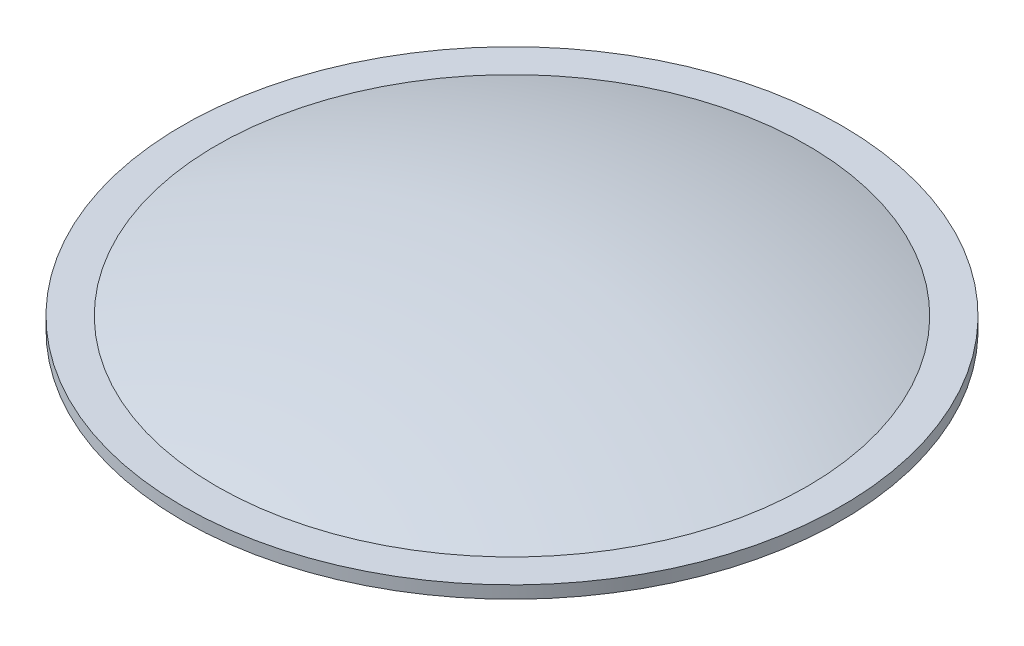
SolidWorks part; units mm, degrees
ref_plane "Front Plane" through (0, 0, 0) normal (0, 0, 1) x (1, 0, 0)
ref_plane "Top Plane" through (0, 0, 0) normal (0, 1, 0) x (1, 0, 0)
ref_plane "Right Plane" through (0, 0, 0) normal (1, 0, 0) x (0, 0, -1)
sketch "Sketch2" plane through (0, 0, 0) normal (0, 0, 1) x (1, 0, 0)
  line L0 (26.43, 1) -> (23.69, 1)
  line L1 (0, 0) -> (26.43, 0)
  line L4 (26.43, 0) -> (26.43, 1)
  line L5 (0, 49.299) -> (0, -39.7739) construction
  line L6 (0, -55) -> (0, 55) construction
  line L7 (0, 4.9884) -> (35.8611, 4.9884) construction
  line L9 (0, 4.9884) -> (0, 0)
  arc A1 (23.69, 1) -> (0, 4.9884) centre (0, -67.3616) ccw
  dimension "D3" = 2.74
  dimension "D4" = 144.7
  dimension "D1" = 26.43
  dimension "D2" = 1
revolve "Revolve1" add sketch "Sketch2" angle 360 about L5
